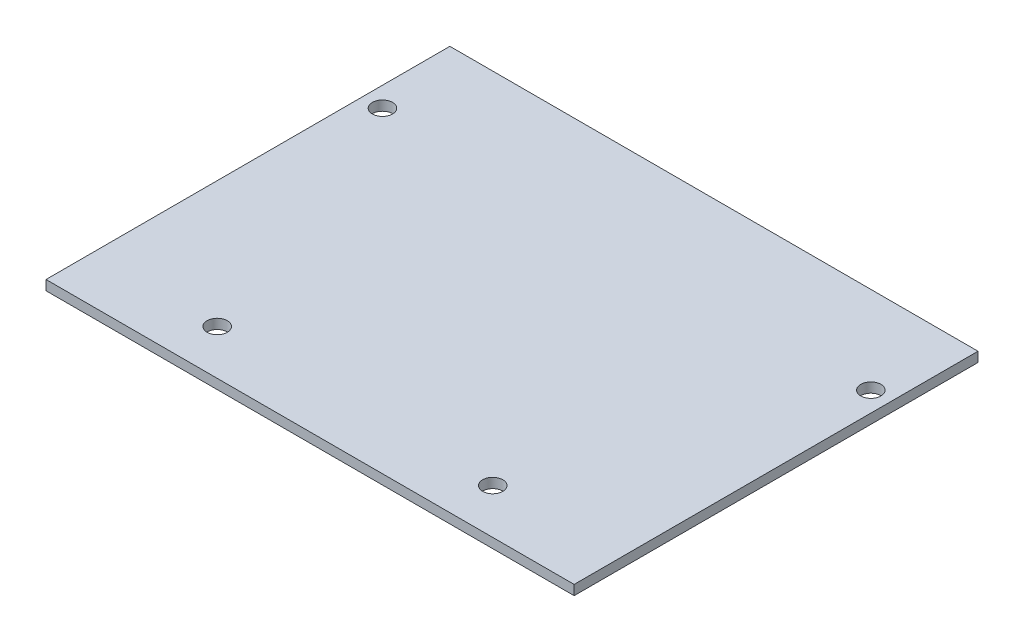
SolidWorks part; units mm, degrees
ref_plane "Front Plane" through (0, 0, 0) normal (0, 0, 1) x (1, 0, 0)
ref_plane "Top Plane" through (0, 0, 0) normal (0, 1, 0) x (1, 0, 0)
ref_plane "Right Plane" through (0, 0, 0) normal (1, 0, 0) x (0, 0, -1)
sketch "Sketch1" plane through (0, 0, 0) normal (0, 1, 0) x (1, 0, 0)
  line L0 (0, 0) -> (50000, 0) construction
  line L1 (-43.18, -33.02) -> (43.18, -33.02)
  line L2 (-43.18, -33.02) -> (-43.18, 33.02)
  line L3 (-43.18, 33.02) -> (43.18, 33.02)
  line L4 (43.18, -33.02) -> (43.18, 33.02)
  line L5 (-43.18, -33.02) -> (43.18, 33.02) construction
  line L6 (-43.18, 33.02) -> (43.18, -33.02) construction
  line L7 (0, 0) -> (0, 50000) construction
  circle A0 centre (-22.5298, -25.6794) radius 1.65
  circle A1 centre (-39.9288, 18.7452) radius 1.65
  circle A2 centre (39.9288, 18.7452) radius 1.65
  circle A3 centre (22.5298, -25.6794) radius 1.65
  point P0 (0, 0)
  dimension "D7" = 3.3
  dimension "D1" = 86.36
  dimension "D2" = 66.04
  dimension "D3" = 20.6502
  dimension "D4" = 7.3406
  dimension "D5" = 3.2512
  dimension "D6" = 51.7652
extrude "Boss-Extrude1" add sketch "Sketch1" along normal blind 1.6
